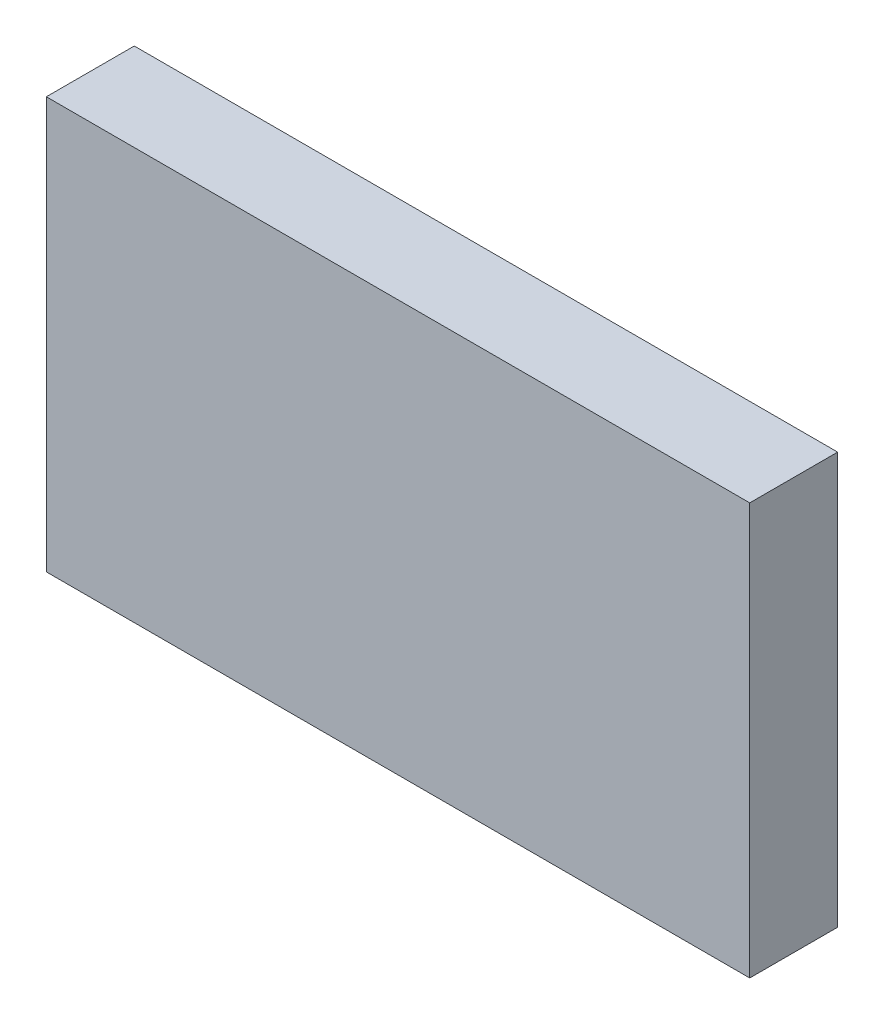
SolidWorks part; units mm, degrees
ref_plane "Front Plane" through (0, 0, 0) normal (0, 0, 1) x (1, 0, 0)
ref_plane "Top Plane" through (0, 0, 0) normal (0, 1, 0) x (1, 0, 0)
ref_plane "Right Plane" through (0, 0, 0) normal (1, 0, 0) x (0, 0, -1)
sketch "Sketch1" plane through (0, 0, 0) normal (0, 0, 1) x (1, 0, 0)
  line L1 (-25.4, -14.859) -> (25.4, -14.859)
  line L2 (-25.4, -14.859) -> (-25.4, 14.859)
  line L3 (-25.4, 14.859) -> (25.4, 14.859)
  line L4 (25.4, -14.859) -> (25.4, 14.859)
  line L5 (-25.4, -14.859) -> (25.4, 14.859) construction
  line L6 (-25.4, 14.859) -> (25.4, -14.859) construction
  point P0 (0, 0)
  dimension "D1" = 50.8
  dimension "D2" = 29.718
extrude "Boss-Extrude1" add sketch "Sketch1" along normal blind 6.35
